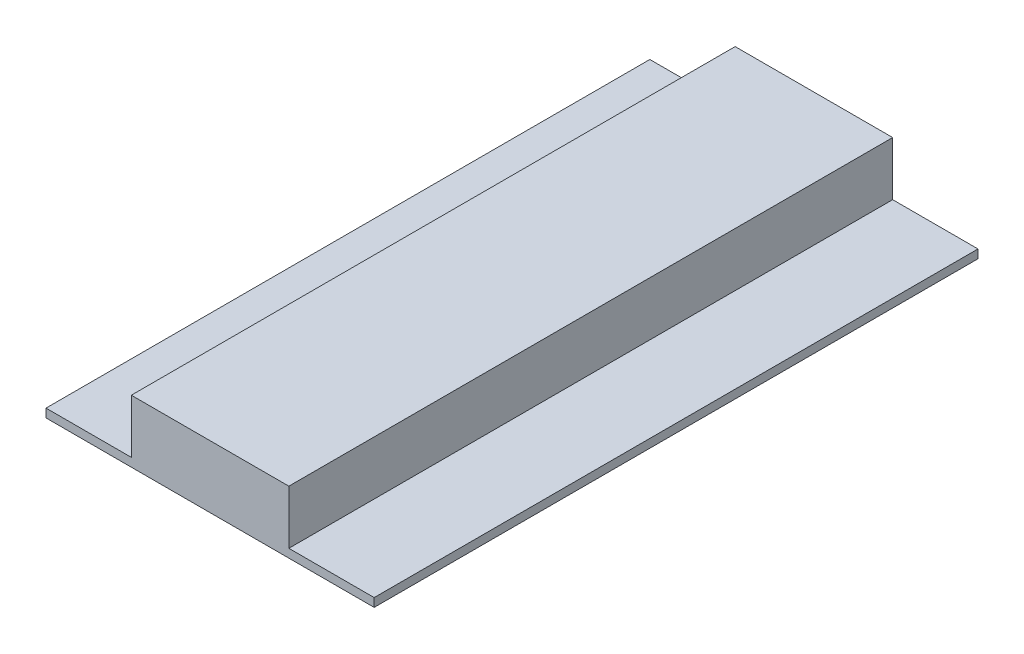
SolidWorks part; units mm, degrees
ref_plane "Front Plane" through (0, 0, 0) normal (0, 0, 1) x (1, 0, 0)
ref_plane "Top Plane" through (0, 0, 0) normal (0, 1, 0) x (1, 0, 0)
ref_plane "Right Plane" through (0, 0, 0) normal (1, 0, 0) x (0, 0, -1)
sketch "Sketch1" plane through (0, 0, 0) normal (0, 0, 1) x (1, 0, 0)
  line L0 (-25, 0) -> (25, 0)
  line L1 (55, 0) -> (-55, 0) construction
  line L2 (-25, 0) -> (-25, 1.3)
  line L5 (0, -55) -> (0, 55) construction
  line L7 (-25, 1.3) -> (25, 1.3)
  line L8 (25, 1.3) -> (25, 0)
  line L10 (-12, 9.5) -> (12, 9.5)
  line L11 (-12, 9.5) -> (-12, 1.3)
  line L12 (-12, 1.3) -> (12, 1.3)
  line L13 (12, 9.5) -> (12, 1.3)
  line L14 (-12, 9.5) -> (12, 1.3) construction
  line L15 (-12, 1.3) -> (12, 9.5) construction
  point P3 (0, 5.4)
  point P6 (0, 0)
  point P12 (0, 30)
  dimension "D1" = 1.3
  dimension "D2" = 50
  dimension "D3" = 8.2
  dimension "D4" = 24
extrude "Boss-Extrude1" add sketch "Sketch1" along normal mid plane 92 contours L13 L10 L11 L7
